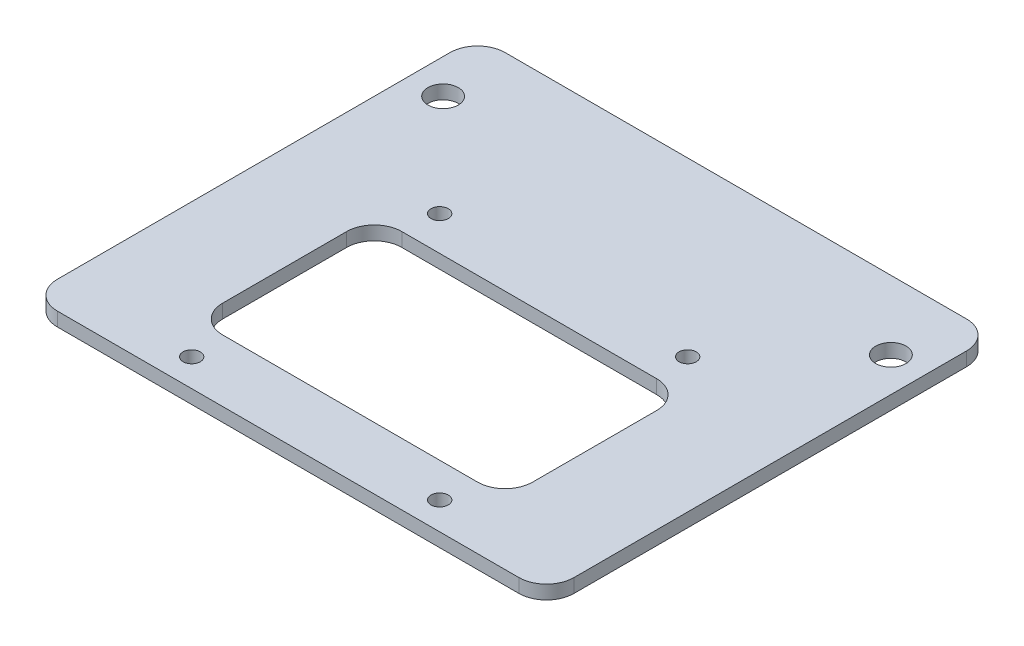
SolidWorks part; units mm, degrees
material "环氧树脂FR-4"
ref_plane "前视基准面" through (0, 0, 0) normal (0, 0, 1) x (1, 0, 0)
ref_plane "上视基准面" through (0, 0, 0) normal (0, 1, 0) x (1, 0, 0)
ref_plane "右视基准面" through (0, 0, 0) normal (1, 0, 0) x (0, 0, -1)
sketch "草图1" plane through (0, 0, 0) normal (0, 1, 0) x (1, 0, 0)
  line L1 (-37.5, 32.5) -> (37.5, 32.5)
  line L2 (-37.5, 32.5) -> (-37.5, -32.5)
  line L3 (-37.5, -32.5) -> (37.5, -32.5)
  line L4 (37.5, 32.5) -> (37.5, -32.5)
  line L5 (-37.5, 32.5) -> (37.5, -32.5) construction
  line L6 (-37.5, -32.5) -> (37.5, 32.5) construction
  point P0 (0, 0)
  dimension "D1" = 65
  dimension "D2" = 75
extrude "凸台-拉伸1" add sketch "草图1" along normal blind 2
sketch "草图2" plane through (0, 2, 0) normal (0, 1, 0) x (1, 0, 0)
  line L0 (37.5, 32.5) -> (-37.5, 32.5) construction
  point P0 (-32.5, 22.5)
  point P1 (32.5, 22.5)
  dimension "D1" = 10
  dimension "D2" = 10
  dimension "D3" = 65
  dimension "D4" = 32.5
hole_wizard "Ø4.4 (4.4) 直径孔1" positions "3D草图1" profile "草图3" hole size "Ø4.4" standard "GB" end condition through all
sketch3d "3D草图1"
  point P0 (-32.5, 2, -22.5)
  point P3 (32.5, 2, -22.5)
sketch "草图3" plane through (-32.5, 2, -22.5) normal (1, 0, 0) x (0, 0, 1)
  line L0 (0, 0) -> (0, 2)
  line L1 (0, 2) -> (2.2, 2)
  line L2 (2.2, 2) -> (2.2, 0)
  line L5 (2.2, 0) -> (0, 0)
  line L11 (0, -6.35) -> (0, 107.95) construction
  dimension "通孔孔直径" = 4.4
  dimension "通孔孔深度" = 2
sketch "草图4" plane through (0, 2, 0) normal (0, 1, 0) x (1, 0, 0)
  circle A0 centre (-32.5, 22.5) radius 2.2 construction
  point P0 (-18, 7.5)
  point P6 (-18, -28.5)
  dimension "D1" = 15
  dimension "D2" = 18
  dimension "D3" = 36
  dimension "D4" = 18
hole_wizard "Ø2.5 (2.5) 直径孔1" positions "3D草图2" profile "草图5" hole size "Ø2.5" standard "GB" end condition through all
sketch3d "3D草图2"
  point P0 (-18, 2, -7.5)
  point P3 (-18, 2, 28.5)
sketch "草图5" plane through (-18, 2, -7.5) normal (1, 0, 0) x (0, 0, 1)
  line L0 (0, 0) -> (0, 2)
  line L1 (0, 2) -> (1.25, 2)
  line L2 (1.25, 2) -> (1.25, 0)
  line L5 (1.25, 0) -> (0, 0)
  line L11 (0, -6.35) -> (0, 107.95) construction
  dimension "通孔孔直径" = 2.5
  dimension "通孔孔深度" = 2
mirror "镜向1" about plane through (0, 0, 0) normal (1, 0, 0) of "Ø2.5 (2.5) 直径孔1"
fillet "圆角1" radius 4 4 edges at (37.5, 1, -32.5) (37.5, 1, 32.5) (-37.5, 1, 32.5) (-37.5, 1, -32.5)
sketch "草图6" plane through (0, 2, 0) normal (0, 1, 0) x (1, 0, 0)
  line L0 (-37.5, 28.5) -> (-37.5, -28.5) construction
  line L1 (-22.5, 2.5) -> (22.5, 2.5)
  line L2 (-22.5, 2.5) -> (-22.5, -23.5)
  line L3 (-22.5, -23.5) -> (22.5, -23.5)
  line L4 (22.5, 2.5) -> (22.5, -23.5)
  line L5 (37.5, -28.5) -> (37.5, 28.5) construction
  circle A0 centre (-18, 7.5) radius 1.25 construction
  circle A1 centre (-18, -28.5) radius 1.25 construction
  dimension "D1" = 5
  dimension "D2" = 5
  dimension "D3" = 15
  dimension "D4" = 15
extrude "切除-拉伸1" cut sketch "草图6" against normal through all
fillet "圆角2" radius 4 4 edges at (22.5, 1, -2.5) (22.5, 1, 23.5) (-22.5, 1, 23.5) (-22.5, 1, -2.5)
